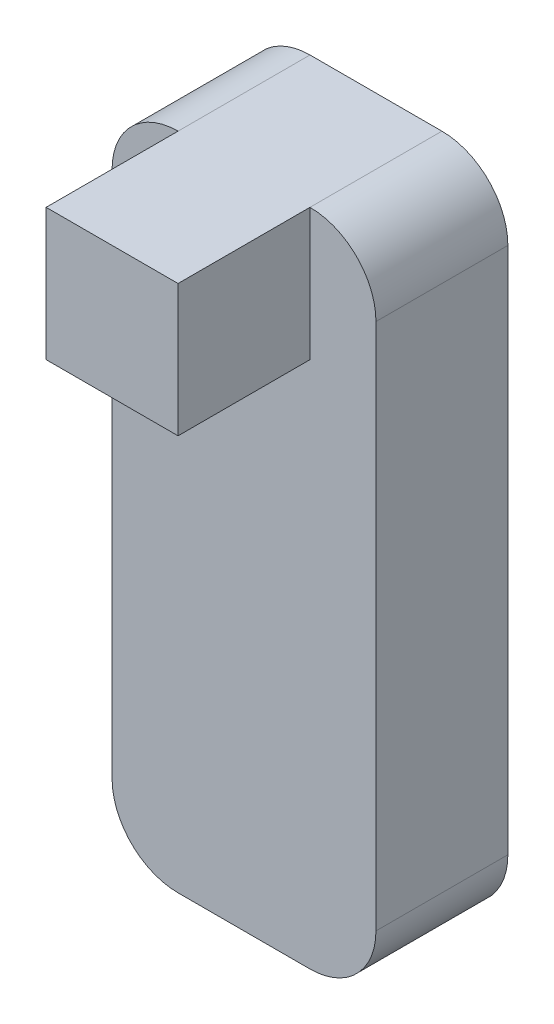
SolidWorks part; units mm, degrees
ref_plane "Alzado" through (0, 0, 0) normal (0, 0, 1) x (1, 0, 0)
ref_plane "Planta" through (0, 0, 0) normal (0, 1, 0) x (1, 0, 0)
ref_plane "Vista lateral" through (0, 0, 0) normal (1, 0, 0) x (0, 0, -1)
sketch "Croquis1" plane through (0, 0, 0) normal (0, 0, 1) x (1, 0, 0)
  line L0 (0, 10) -> (17.5, 10)
  line L1 (10, 0) -> (30, 0)
  line L2 (0, 10) -> (0, 90)
  line L3 (10, 100) -> (30, 100)
  line L4 (40, 10) -> (40, 90)
  line L6 (18, 8.5) -> (22, 8.5)
  line L7 (22.5, 10) -> (40, 10)
  arc A0 (30, 0) -> (40, 10) centre (30, 10) ccw
  arc A1 (10, 0) -> (0, 10) centre (10, 10) cw
  arc A2 (40, 90) -> (30, 100) centre (30, 90) ccw
  arc A3 (10, 100) -> (0, 90) centre (10, 90) ccw
  circle A4 centre (20, 10) radius 2.5
  point P9 (0, 0)
  point P12 (40, 100)
  point P15 (0, 100)
  dimension "D3" = 10
  dimension "D4" = 5
  dimension "D1" = 100
  dimension "D2" = 40
extrude "Saliente-Extruir1" add sketch "Croquis1" along normal blind 20 contours A4 L7 L4 A2 L3 A3 L2 L0 | A4 L0 A1 L1 A0 L7 | L6 A4 | A4 L6
sketch "Croquis2" plane through (0, 0, 0) normal (0, 0, -1) x (-1, 0, 0)
  line L2 (-20, 8.5) -> (-22, 8.5)
  line L3 (-22, 8.5) -> (-18, 8.5)
  circle A0 centre (-20, 10) radius 2.5
  dimension "D1" = 5
extrude "Cortar-Extruir1" cut sketch "Croquis2" against normal blind 8 contours L3 A0 L2
sketch "Croquis3" plane through (0, 100, 0) normal (0, 1, 0) x (1, 0, 0)
  line L2 (30, -20) -> (10, -20)
  line L3 (30, -20) -> (30, -40)
  line L4 (30, -40) -> (10, -40)
  line L5 (10, -20) -> (10, -40)
  dimension "D1" = 20
  dimension "D2" = 20
extrude "Saliente-Extruir2" add sketch "Croquis3" against normal blind 20
